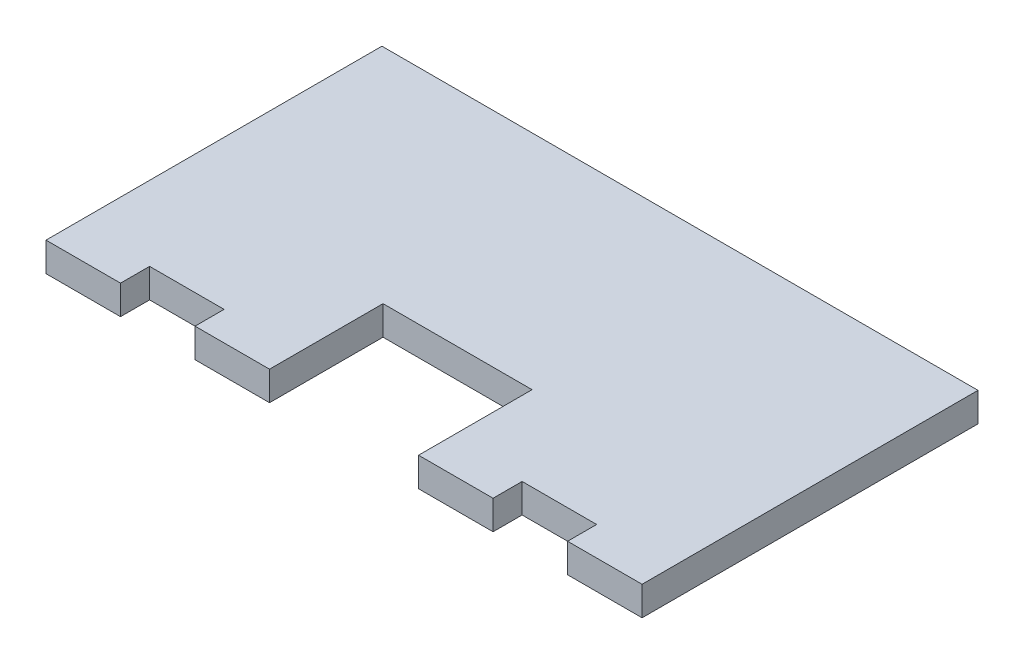
SolidWorks part; units mm, degrees
ref_plane "Front Plane" through (0, 0, 0) normal (0, 0, 1) x (1, 0, 0)
ref_plane "Top Plane" through (0, 0, 0) normal (0, 1, 0) x (1, 0, 0)
ref_plane "Right Plane" through (0, 0, 0) normal (1, 0, 0) x (0, 0, -1)
sketch "Sketch1" plane through (0, 0, 0) normal (0, 1, 0) x (1, 0, 0)
  line L1 (-48.7146, 43.1681) -> (99.215, 43.1681)
  line L2 (-48.7146, 43.1681) -> (-48.7146, -40.1947)
  line L3 (-48.7146, -40.1947) -> (99.215, -40.1947)
  line L4 (99.215, 43.1681) -> (99.215, -40.1947)
  dimension "D1" = 83.3628
  dimension "D2" = 147.9296
extrude "Boss-Extrude1" add sketch "Sketch1" along normal blind 7.2136
sketch "Sketch2" plane through (0, 0, 0) normal (0, -1, 0) x (1, 0, 0)
  line L0 (-48.7146, 40.1947) -> (99.215, 40.1947) construction
  line L1 (-30.2234, 40.1947) -> (-11.7322, 40.1947)
  line L2 (-30.2234, 40.1947) -> (-30.2234, 32.9811)
  line L3 (-30.2234, 32.9811) -> (-11.7322, 32.9811)
  line L4 (-11.7322, 40.1947) -> (-11.7322, 32.9811)
  line L5 (25.2502, 40.1947) -> (25.2502, -43.1681) construction
  line L6 (99.215, -43.1681) -> (-48.7146, -43.1681) construction
  line L7 (-48.7146, -43.1681) -> (-48.7146, 40.1947) construction
  line L8 (43.7414, 40.1947) -> (6.759, 40.1947)
  line L9 (25.2502, 40.1947) -> (25.2502, 12.0261)
  line L10 (43.7414, 12.0261) -> (6.759, 12.0261)
  line L11 (6.759, 40.1947) -> (6.759, 12.0261)
  line L12 (43.7414, 40.1947) -> (43.7414, 12.0261)
  line L13 (80.7238, 32.9811) -> (62.2326, 32.9811)
  line L14 (62.2326, 40.1947) -> (62.2326, 32.9811)
  line L15 (80.7238, 40.1947) -> (62.2326, 40.1947)
  line L16 (80.7238, 40.1947) -> (80.7238, 32.9811)
  line M6 (99.215, 40.1947) -> (-48.7146, 40.1947)
  dimension "D1" = 7.2136
  dimension "D2" = 28.1686
  dimension "D3" = 18.4912
  dimension "D4" = 18.4912
  dimension "D6" = 18.4912
  dimension "D5" = 18.4912
extrude "Cut-Extrude1" cut sketch "Sketch2" against normal through all contours L4 L2 L3 M6 | L8 L11 L10 L9 | L12 L9 L10 M6 | L16 L14 L13 M6
equation "\"D1@Sketch1\"=\"Side Height@Assembled Container.Assembly\""
equation "\"D2@Sketch1\"=\"Short Side Width@Assembled Container.Assembly\""
equation "\"D1@Boss-Extrude1\"=\"Acrylic Thickness@Assembled Container.Assembly\""
equation "\"D1@Sketch2\"=\"Acrylic Thickness@Assembled Container.Assembly\""
equation "\"D2@Sketch2\" = \"Short Side Finger Hole@Assembled Container.Assembly\""
equation "\"D3@Sketch2\"=\"Lid Short Side Outer Cutout@Assembled Container.Assembly\""
equation "\"D4@Sketch2\"=\"Lid Short Side Outer Overhang@Assembled Container.Assembly\""
equation "\"D5@Sketch2\"=\"Lid Short Side Middle Overhang@Assembled Container.Assembly\""
